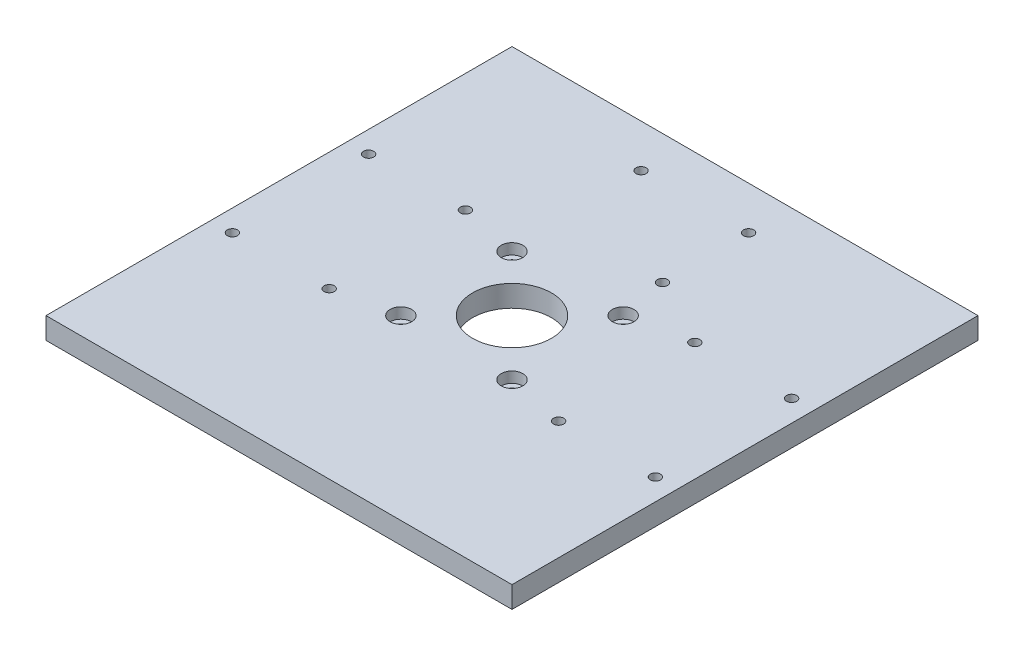
SolidWorks part; units mm, degrees
ref_plane "Front Plane" through (0, 0, 0) normal (0, 0, 1) x (1, 0, 0)
ref_plane "Top Plane" through (0, 0, 0) normal (0, 1, 0) x (1, 0, 0)
ref_plane "Right Plane" through (0, 0, 0) normal (1, 0, 0) x (0, 0, -1)
sketch "Sketch1" plane through (0, 0, 0) normal (0, 1, 0) x (1, 0, 0)
  line L1 (-65, -65) -> (65, -65)
  line L2 (-65, -65) -> (-65, 65)
  line L3 (-65, 65) -> (65, 65)
  line L4 (65, -65) -> (65, 65)
  line L5 (-65, -65) -> (65, 65) construction
  line L6 (-65, 65) -> (65, -65) construction
  circle A0 centre (0, 0) radius 11
  point P0 (0, 0)
  dimension "D3" = 22
  dimension "D1" = 130
  dimension "D2" = 130
extrude "Boss-Extrude1" add sketch "Sketch1" along normal blind 6
sketch "Sketch2" plane through (0, 6, 0) normal (0, 1, 0) x (1, 0, 0)
  line L0 (-15.5, 15.5) -> (15.5, 15.5) construction
  circle A0 centre (-15.5, 15.5) radius 1.42
  circle A1 centre (15.5, 15.5) radius 1.42
  circle A2 centre (15.5, -15.5) radius 1.42
  circle A3 centre (-15.5, -15.5) radius 1.42
  dimension "D1" = 2.84
  dimension "D2" = 15.5
  dimension "D3" = 15.5
  dimension "D6" = 31
  dimension "D4" = 2
  dimension "D5" = 2
extrude "Cut-Extrude1" cut sketch "Sketch2" against normal blind 6
sketch "Sketch3" plane through (0, 6, 0) normal (0, 1, 0) x (1, 0, 0)
  line L0 (-15.5, 15.5) -> (15.5, 15.5) construction
  circle A0 centre (-15.5, 15.5) radius 3
  circle A1 centre (15.5, 15.5) radius 3
  circle A2 centre (15.5, -15.5) radius 3
  circle A3 centre (-15.5, -15.5) radius 3
  dimension "D1" = 6
  dimension "D4" = 31
  dimension "D2" = 2
  dimension "D3" = 2
extrude "Cut-Extrude2" cut sketch "Sketch3" against normal blind 3
sketch "Sketch4" plane through (0, 6, 0) normal (0, 1, 0) x (1, 0, 0)
  line L0 (65, 65) -> (-65, 65) construction
  line L2 (-65, 65) -> (-65, -65) construction
  line L3 (0, 46.5829) -> (0, -60.4578) construction
  circle A0 centre (-59, 19) radius 1.42
  circle A1 centre (-32, 19) radius 1.42
  circle A2 centre (-32, -19) radius 1.42
  circle A3 centre (-59, -19) radius 1.42
  circle A4 centre (59, 19) radius 1.42
  circle A5 centre (59, -19) radius 1.42
  circle A6 centre (32, -19) radius 1.42
  circle A7 centre (32, 19) radius 1.42
  dimension "D1" = 2.84
  dimension "D4" = 46
  dimension "D5" = 6
  dimension "D2" = 2
  dimension "D3" = 2
extrude "Cut-Extrude3" cut sketch "Sketch4" against normal blind 10
sketch "Sketch5" plane through (0, 6, 0) normal (0, 1, 0) x (1, 0, 0)
  line L0 (65, -65) -> (65, 65) construction
  line L1 (65, 65) -> (-65, 65) construction
  circle A0 centre (13, 53) radius 1.42
  circle A1 centre (-17, 53) radius 1.42
  circle A2 centre (13, 29) radius 1.42
  dimension "D2" = 2.84
  dimension "D3" = 2.84
  dimension "D6" = 2.84
  dimension "D1" = 52
  dimension "D4" = 30
  dimension "D5" = 12
  dimension "D7" = 36
extrude "Cut-Extrude4" cut sketch "Sketch5" against normal blind 10
